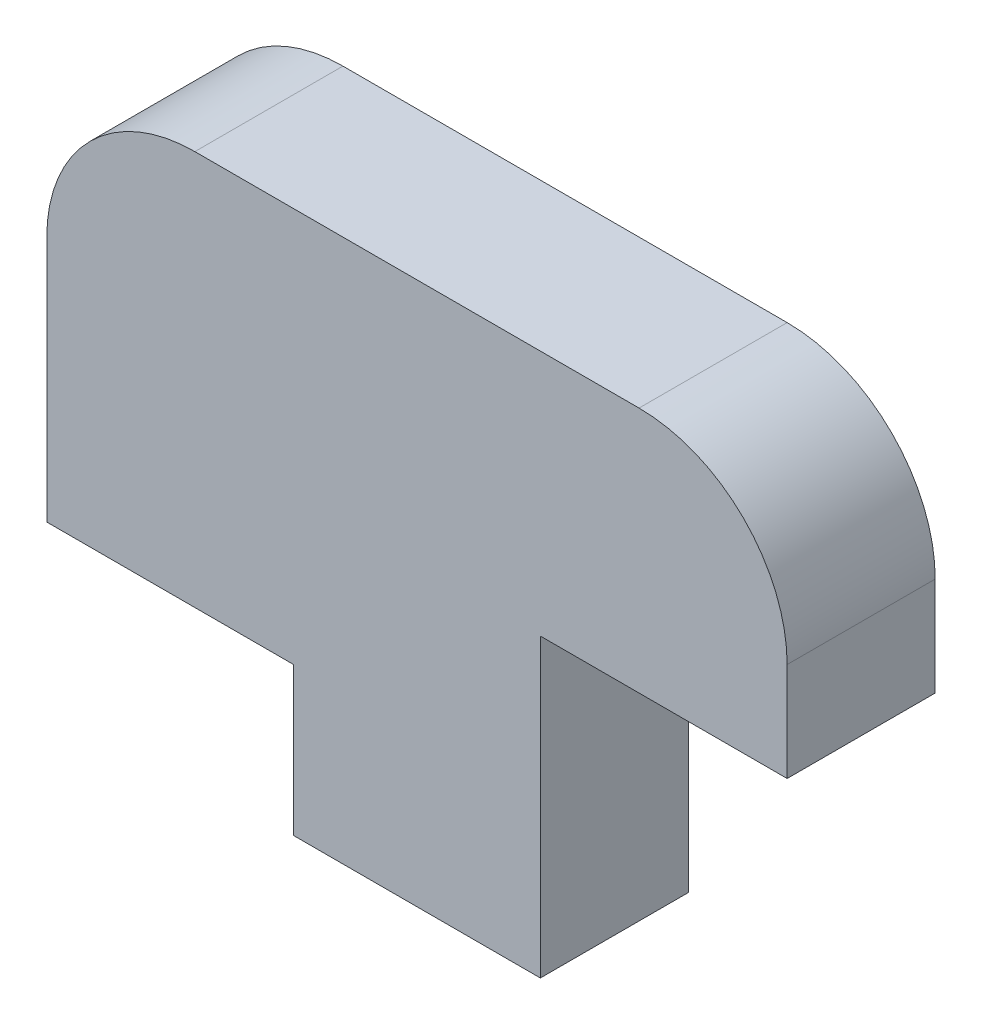
SolidWorks part; units mm, degrees
material "ABS PC"
ref_plane "Front Plane" through (0, 0, 0) normal (0, 0, 1) x (1, 0, 0)
ref_plane "Top Plane" through (0, 0, 0) normal (0, 1, 0) x (1, 0, 0)
ref_plane "Right Plane" through (0, 0, 0) normal (1, 0, 0) x (0, 0, -1)
sketch "Sketch1" plane through (0, 0, 0) normal (0, 0, 1) x (1, 0, 0)
  line L0 (-10, 3) -> (-5, 3)
  line L1 (-5, 3) -> (-5, 0)
  line L2 (-5, 0) -> (0, 0)
  line L3 (0, 0) -> (0, 6)
  line L5 (0, 6) -> (5, 6)
  line L6 (5, 6) -> (5, 8)
  line L7 (-10, 3) -> (-10, 8)
  line L8 (-7, 11) -> (2, 11)
  arc A0 (5, 8) -> (2, 11) centre (2, 8) ccw
  arc A1 (-10, 8) -> (-7, 11) centre (-7, 8) cw
  dimension "D1" = 3
  dimension "D2" = 8
  dimension "D3" = 3
  dimension "D4" = 3
  dimension "D5" = 5
  dimension "D6" = 5
  dimension "D7" = 5
extrude "Boss-Extrude1" add sketch "Sketch1" along normal blind 3
